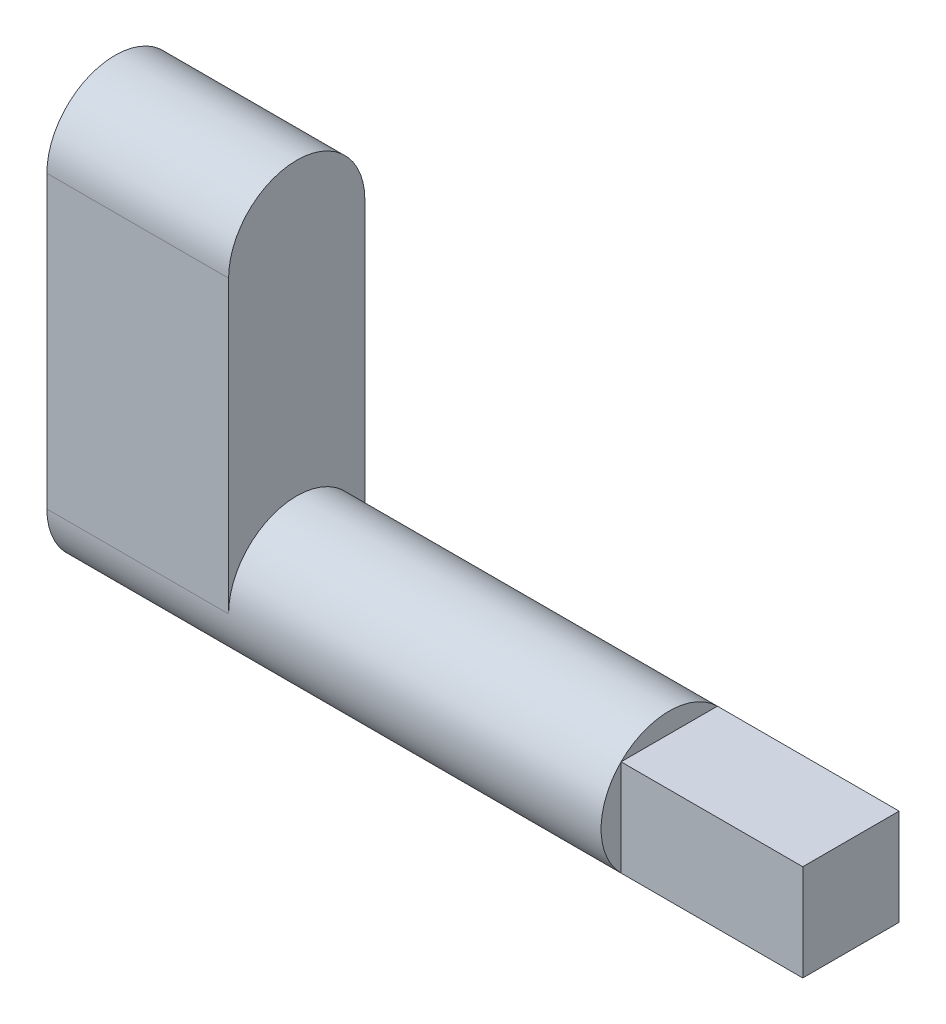
SolidWorks part; units mm, degrees
ref_plane "Front Plane" through (0, 0, 0) normal (0, 0, 1) x (1, 0, 0)
ref_plane "Top Plane" through (0, 0, 0) normal (0, 1, 0) x (1, 0, 0)
ref_plane "Right Plane" through (0, 0, 0) normal (1, 0, 0) x (0, 0, -1)
sketch "Sketch1" plane through (0, 0, 0) normal (1, 0, 0) x (0, 0, -1)
  circle A0 centre (0, 0) radius 3.75
  dimension "D1" = 7.5
extrude "Boss-Extrude1" add sketch "Sketch1" against normal blind 30.5
sketch "Sketch2" plane through (0, 0, 0) normal (1, 0, 0) x (0, 0, -1)
  line L1 (2.6517, -2.6517) -> (-2.6517, -2.6517)
  line L2 (2.6517, -2.6517) -> (2.6517, 2.6517)
  line L3 (2.6517, 2.6517) -> (-2.6517, 2.6517)
  line L4 (-2.6517, -2.6517) -> (-2.6517, 2.6517)
  line L5 (2.6517, -2.6517) -> (-2.6517, 2.6517) construction
  line L6 (2.6517, 2.6517) -> (-2.6517, -2.6517) construction
  circle A0 centre (0, 0) radius 3.75 construction
  point P0 (0, 0)
  point P8 (0, 0)
  point P9 (-2.5178, 2.779)
extrude "Boss-Extrude2" add sketch "Sketch2" along normal blind 10
sketch "Sketch3" plane through (-30.5, 0, 0) normal (-1, 0, 0) x (0, 0, 1)
  line L0 (-3.75, 0) -> (-3.75, 16)
  line L1 (3.75, 16) -> (3.75, 0)
  arc A0 (-3.75, 0) -> (3.75, 0) centre (0, 0) ccw
  arc A1 (-3.75, 16) -> (3.75, 16) centre (0, 16) cw
  circle A2 centre (0, 0) radius 3.75 construction
  point P1 (3.75, 0)
  point P10 (0, 13.7766)
  dimension "D1" = 16
extrude "Boss-Extrude3" add sketch "Sketch3" against normal blind 10
